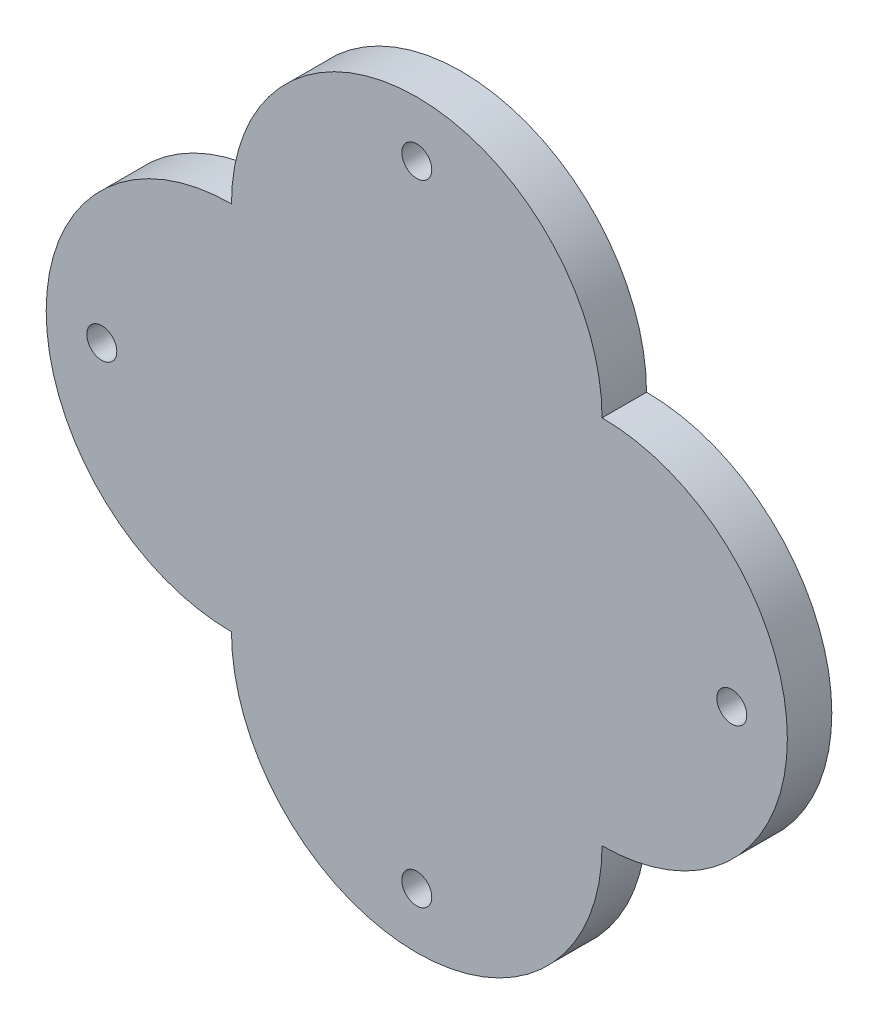
SolidWorks part; units mm, degrees
ref_plane "Ön Düzlem" through (0, 0, 0) normal (0, 0, 1) x (1, 0, 0)
ref_plane "Üst Düzlem" through (0, 0, 0) normal (0, 1, 0) x (1, 0, 0)
ref_plane "Sağ Düzlem" through (0, 0, 0) normal (1, 0, 0) x (0, 0, -1)
sketch "Çizim1" plane through (0, 0, 0) normal (0, 0, 1) x (1, 0, 0)
  arc A0 (55.5556, 45.5939) -> (-44.4444, 45.5939) centre (5.5556, 45.5939) ccw
  arc A1 (55.5556, -54.4061) -> (55.5556, 45.5939) centre (55.5556, -4.4061) ccw
  arc A2 (-44.4444, -54.4061) -> (55.5556, -54.4061) centre (5.5556, -54.4061) ccw
  arc A3 (-44.4444, 45.5939) -> (-44.4444, -54.4061) centre (-44.4444, -4.4061) ccw
  circle A4 centre (-79.4444, -4.4061) radius 9.5
  circle A5 centre (5.5556, 80.5939) radius 9.5
  circle A6 centre (90.5556, -4.4061) radius 9.5
  circle A7 centre (5.5556, -89.4061) radius 9.5
  dimension "D3" = 35
  dimension "D4" = 35
  dimension "D5" = 35
  dimension "D6" = 35
  dimension "D7" = 19
  dimension "D1" = 100
  dimension "D2" = 100
extrude "Yükseklik-Ekstrüzyon1" add sketch "Çizim1" along normal blind 12
sketch "Çizim2" plane through (0, 0, 12) normal (0, 0, 1) x (1, 0, 0)
  circle A0 centre (5.5556, 80.5939) radius 9.5
  circle A1 centre (90.5556, -4.4061) radius 9.5
  circle A2 centre (5.5556, -89.4061) radius 9.5
  circle A3 centre (-79.4444, -4.4061) radius 9.5
  circle A4 centre (5.5556, 80.5939) radius 4.05
  circle A5 centre (90.5556, -4.4061) radius 4.05
  circle A6 centre (5.5556, -89.4061) radius 4.05
  circle A7 centre (-79.4444, -4.4061) radius 4.05
  dimension "D1" = 8.1
  dimension "D2" = 8.1
  dimension "D3" = 8.1
  dimension "D4" = 8.1
extrude "Yükseklik-Ekstrüzyon2" add sketch "Çizim2" against normal blind 6
